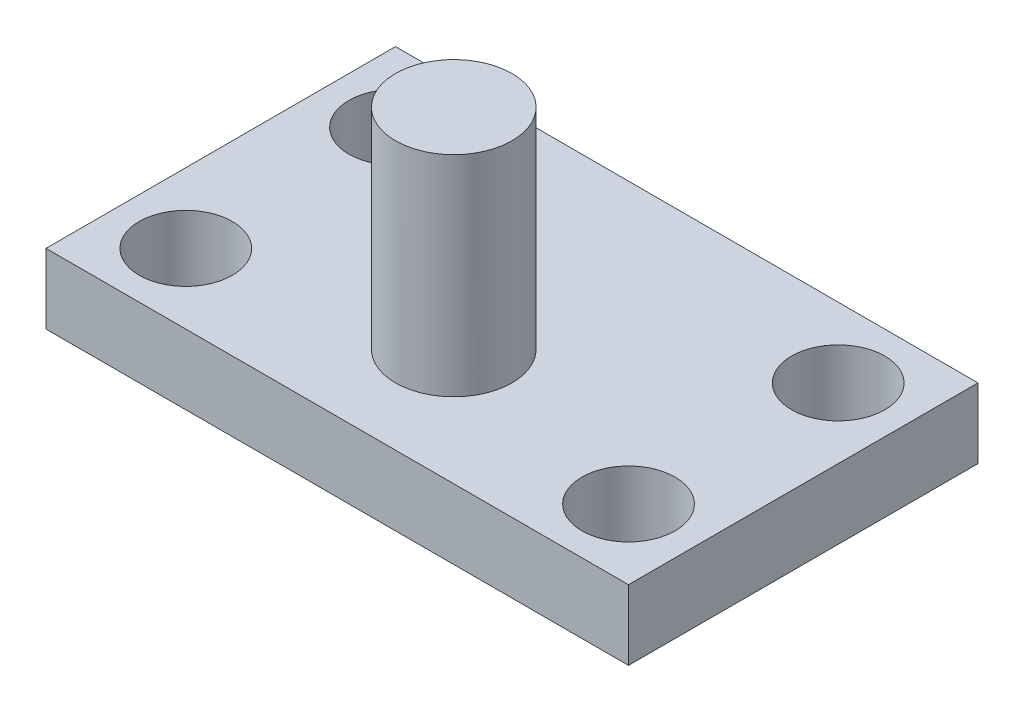
SolidWorks part; units mm, degrees
ref_plane "Front Plane" through (0, 0, 0) normal (0, 0, 1) x (1, 0, 0)
ref_plane "Top Plane" through (0, 0, 0) normal (0, 1, 0) x (1, 0, 0)
ref_plane "Right Plane" through (0, 0, 0) normal (1, 0, 0) x (0, 0, -1)
sketch "Sketch1" plane through (0, 0, 0) normal (0, 1, 0) x (1, 0, 0)
  line L0 (0, 143.1367) -> (0, -130.5625) construction
  line L1 (-125, 75) -> (125, 75)
  line L2 (-125, 75) -> (-125, -75)
  line L3 (-125, -75) -> (125, -75)
  line L4 (125, 75) -> (125, -75)
  line L5 (-125, 75) -> (125, -75) construction
  line L6 (-125, -75) -> (125, 75) construction
  circle A0 centre (0, -25) radius 25
  circle A1 centre (-95, 45) radius 20
  circle A2 centre (-95, -45) radius 20
  circle A3 centre (95, -45) radius 20
  circle A4 centre (95, 45) radius 20
  point P0 (0, 0)
  dimension "D3" = 50
  dimension "D5" = 40
  dimension "D1" = 250
  dimension "D2" = 150
  dimension "D4" = 100
  dimension "D6" = 90
  dimension "D7" = 30
  dimension "D8" = 30
  dimension "D9" = 30
extrude "Boss-Extrude1" add sketch "Sketch1" along normal blind 30
sketch "Sketch2" plane through (0, 0, 0) normal (0, -1, 0) x (1, 0, 0)
  circle A0 centre (0, 25) radius 25 construction
  circle A1 centre (0, 25) radius 25
extrude "Boss-Extrude2" add sketch "Sketch2" against normal blind 120
